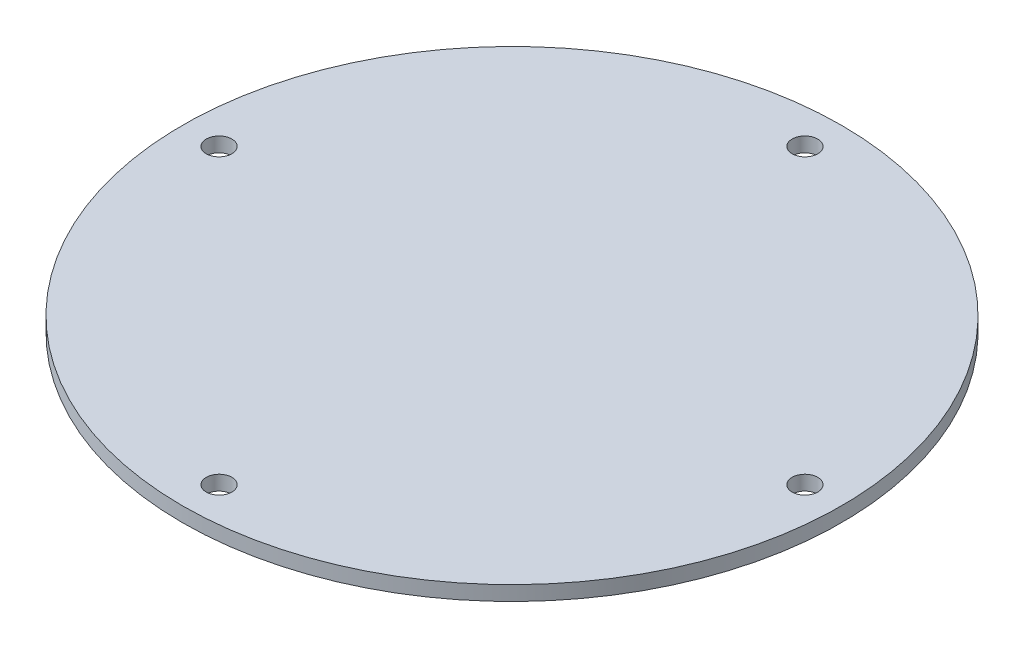
SolidWorks part; units mm, degrees
ref_plane "Front Plane" through (0, 0, 0) normal (0, 0, 1) x (1, 0, 0)
ref_plane "Top Plane" through (0, 0, 0) normal (0, 1, 0) x (1, 0, 0)
ref_plane "Right Plane" through (0, 0, 0) normal (1, 0, 0) x (0, 0, -1)
sketch "Sketch1" plane through (0, 0, 0) normal (0, 1, 0) x (1, 0, 0)
  circle A0 centre (0, 0) radius 45
  dimension "D1" = 90
extrude "Boss-Extrude1" add sketch "Sketch1" along normal blind 2
sketch "Sketch2" plane through (0, 2, 0) normal (0, 1, 0) x (1, 0, 0)
  circle A0 centre (0, 40) radius 1.75
  circle A1 centre (40, 0) radius 1.75
  circle A2 centre (0, -40) radius 1.75
  circle A3 centre (-40, 0) radius 1.75
  point P12 (0, 0)
  dimension "D2" = 3.5
  dimension "D1" = 40
  dimension "D3" = 4
extrude "Cut-Extrude1" cut sketch "Sketch2" against normal through all
